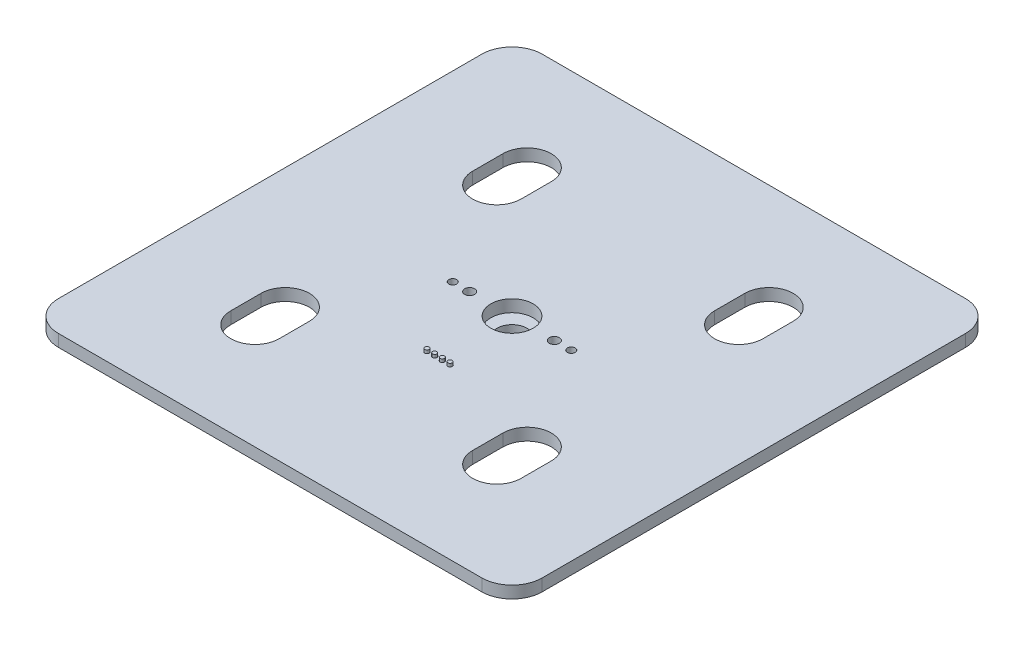
SolidWorks part; units mm, degrees
ref_plane "Front Plane" through (0, 0, 0) normal (0, 0, 1) x (1, 0, 0)
ref_plane "Top Plane" through (0, 0, 0) normal (0, 1, 0) x (1, 0, 0)
ref_plane "Right Plane" through (0, 0, 0) normal (1, 0, 0) x (0, 0, -1)
sketch "Sketch1" plane through (0, 0, 0) normal (0, 1, 0) x (1, 0, 0)
  line L1 (-40, -40) -> (40, -40)
  line L2 (-40, -40) -> (-40, 40)
  line L3 (-40, 40) -> (40, 40)
  line L4 (40, -40) -> (40, 40)
  line L5 (-40, -40) -> (40, 40) construction
  line L6 (-40, 40) -> (40, -40) construction
  point P0 (0, 0)
  dimension "D1" = 40
extrude "Boss-Extrude1" add sketch "Sketch1" along normal mid plane 2
fillet "Fillet1" radius 5 1 edges at (-40, 0, 40)
fillet "Fillet3" radius 5 1 edges at (-40, 0, -40)
fillet "Fillet4" radius 5 1 edges at (40, 0, -40)
fillet "Fillet5" radius 5 1 edges at (40, 0, 40)
sketch "Sketch2" plane through (0, 1, 0) normal (0, 1, 0) x (1, 0, 0)
  line L0 (0, 43.5966) -> (0, -43.8986) construction
  line L1 (-44.3014, 0) -> (44.9055, 0) construction
  line L2 (-20, 17.5) -> (-20, 22.5) construction
  line L3 (-24, 17.5) -> (-24, 22.5)
  line L4 (-16, 17.5) -> (-16, 22.5)
  line L5 (-20, -17.5) -> (-20, -22.5) construction
  line L6 (-16, -17.5) -> (-16, -22.5)
  line L7 (-24, -17.5) -> (-24, -22.5)
  line L8 (20, -17.5) -> (20, -22.5) construction
  line L9 (16, -17.5) -> (16, -22.5)
  line L10 (24, -17.5) -> (24, -22.5)
  line L11 (20, 17.5) -> (20, 22.5) construction
  line L12 (24, 17.5) -> (24, 22.5)
  line L13 (16, 17.5) -> (16, 22.5)
  arc A0 (-24, 17.5) -> (-16, 17.5) centre (-20, 17.5) ccw
  arc A1 (-16, 22.5) -> (-24, 22.5) centre (-20, 22.5) ccw
  arc A2 (-16, -17.5) -> (-24, -17.5) centre (-20, -17.5) ccw
  arc A3 (-24, -22.5) -> (-16, -22.5) centre (-20, -22.5) ccw
  arc A4 (16, -17.5) -> (24, -17.5) centre (20, -17.5) cw
  arc A5 (24, -22.5) -> (16, -22.5) centre (20, -22.5) cw
  arc A6 (24, 17.5) -> (16, 17.5) centre (20, 17.5) cw
  arc A7 (16, 22.5) -> (24, 22.5) centre (20, 22.5) cw
  point P7 (-20, 20)
  point P13 (-20, -20)
  point P19 (-20, 28.7959)
  point P22 (20, -20)
  point P29 (20, 20)
  dimension "D4" = 4
  dimension "D1" = 20
  dimension "D2" = 20
  dimension "D3" = 20
  dimension "D5" = 5
extrude "Cut-Extrude1" cut sketch "Sketch2" against normal through all both and the other way through all
sketch "Sketch3" plane through (0, 1, 0) normal (0, 1, 0) x (1, 0, 0)
  circle A0 centre (0, 0) radius 3.5
  dimension "D1" = 7
extrude "Cut-Extrude2" cut sketch "Sketch3" against normal through all both and the other way through all
sketch "Sketch4" plane through (0, 1, 0) normal (0, 1, 0) x (1, 0, 0)
  line L0 (-13.5506, -12.15) -> (0, -12.15) construction
  line L1 (0, 0) -> (0, -12.15) construction
  line L2 (0, 0) -> (-13.5506, 0) construction
  circle A2 centre (-0.635, -12.15) radius 0.38
  circle A3 centre (-1.905, -12.15) radius 0.38
  circle A5 centre (-9.8, 0) radius 0.65
  circle A6 centre (-7, 0) radius 0.825
  circle A7 centre (7, 0) radius 0.825
  circle A8 centre (9.8, 0) radius 0.65
  circle A9 centre (0.635, -12.15) radius 0.38
  circle A10 centre (1.905, -12.15) radius 0.38
  dimension "D4" = 0.76
  dimension "D7" = 1.3
  dimension "D8" = 1.65
  dimension "D1" = 0.635
  dimension "D2" = 7
  dimension "D3" = 9.8
  dimension "D5" = 1.27
  dimension "D6" = 12.15
extrude "Cut-Extrude3" cut sketch "Sketch4" against normal through all both and the other way through all
sketch "Sketch6" plane through (0, -1, 0) normal (0, -1, 0) x (1, 0, 0)
  line L0 (-4.85, 8.7451) -> (-4.85, 10.45)
  line L1 (-4.85, 10.45) -> (-3.2, 10.45)
  line L2 (4.85, 10.45) -> (4.85, 8.7451)
  line L3 (-3.2, 10.45) -> (-3.2, 11.45)
  line L4 (-3.2, 11.45) -> (3.2, 11.45)
  line L5 (3.2, 11.45) -> (3.2, 10.45)
  line L6 (0, -1.1) -> (0, 1.1) construction
  line L7 (3.2, 10.45) -> (4.85, 10.45)
  arc A0 (-4.85, 8.7451) -> (4.85, 8.7451) centre (0, 0) ccw
  dimension "D1" = 20
  dimension "D2" = 11.45
  dimension "D3" = 4.85
  dimension "D4" = 6.4
  dimension "D5" = 3.2
  dimension "D6" = 10.45
extrude "Boss-Extrude2" add sketch "Sketch6" along normal blind 4 from offset 1 separate body
sketch "Sketch7" plane through (0, 1, 0) normal (0, 1, 0) x (1, 0, 0)
  line L0 (0, 0) -> (0, -18.7112) construction
  line L1 (0, -3.85) -> (0, 3.85) construction
  line L2 (-5.491, -12.15) -> (6.241, -12.15) construction
  circle A0 centre (-1.905, -12.15) radius 0.35
  circle A1 centre (-0.635, -12.15) radius 0.35
  circle A2 centre (0.635, -12.15) radius 0.35
  circle A3 centre (1.905, -12.15) radius 0.35
  dimension "D2" = 0.7
  dimension "D1" = 12.15
extrude "Boss-Extrude3" add sketch "Sketch7" against normal blind 5 and the other way blind 0.5 separate body
sketch "Sketch8" plane through (0, 0, 11.45) normal (0, 0, 1) x (1, 0, 0)
  line L0 (0, -6.8632) -> (0, 0.2753) construction
  line L1 (0, -3.85) -> (0, 3.85) construction
  line L2 (-1.905, -6.8048) -> (-1.905, 0) construction
  line L3 (-2.255, -4.7) -> (-1.555, -4.7)
  line L4 (-2.255, -4.7) -> (-2.255, -4)
  line L5 (-2.255, -4) -> (-1.555, -4)
  line L6 (-1.555, -4.7) -> (-1.555, -4)
  line L7 (-2.255, -4.7) -> (-1.555, -4) construction
  line L8 (-2.255, -4) -> (-1.555, -4.7) construction
  line L9 (-0.985, -4.7) -> (-0.285, -4.7)
  line L10 (-0.985, -4.7) -> (-0.985, -4)
  line L11 (-0.985, -4) -> (-0.285, -4)
  line L12 (-0.285, -4.7) -> (-0.285, -4)
  line L13 (-0.985, -4.7) -> (-0.285, -4) construction
  line L14 (-0.985, -4) -> (-0.285, -4.7) construction
  line L15 (44, 0) -> (-44, 0) construction
  line L16 (-0.635, 0) -> (-0.635, -6.9727) construction
  line L17 (-2.255, 1.5) -> (-2.255, -4) construction
  line L18 (-0.985, 1.5) -> (-0.985, -4) construction
  line L19 (3.2, -2) -> (-3.2, -2) construction
  line L20 (0.285, -4.7) -> (0.285, -4)
  line L21 (0.985, -4) -> (0.285, -4)
  line L22 (0.985, -4.7) -> (0.985, -4)
  line L23 (0.985, -4.7) -> (0.285, -4.7)
  line L24 (2.255, -4.7) -> (1.555, -4.7)
  line L25 (2.255, -4.7) -> (2.255, -4)
  line L26 (2.255, -4) -> (1.555, -4)
  line L27 (1.555, -4.7) -> (1.555, -4)
  point P5 (-1.905, -4.35)
  point P10 (-0.635, -4.35)
  dimension "D1" = 0.35
  dimension "D2" = 0.35
  dimension "D3" = 0.7
  dimension "D4" = 2
extrude "Boss-Extrude4" add sketch "Sketch8" along normal blind 1.1
sketch "Sketch9" plane through (0, -6, 0) normal (0, -1, 0) x (1, 0, 0)
  circle A0 centre (0, 0) radius 2.5
  dimension "D1" = 5
extrude "Cut-Extrude4" cut sketch "Sketch9" against normal through all both and the other way through all
